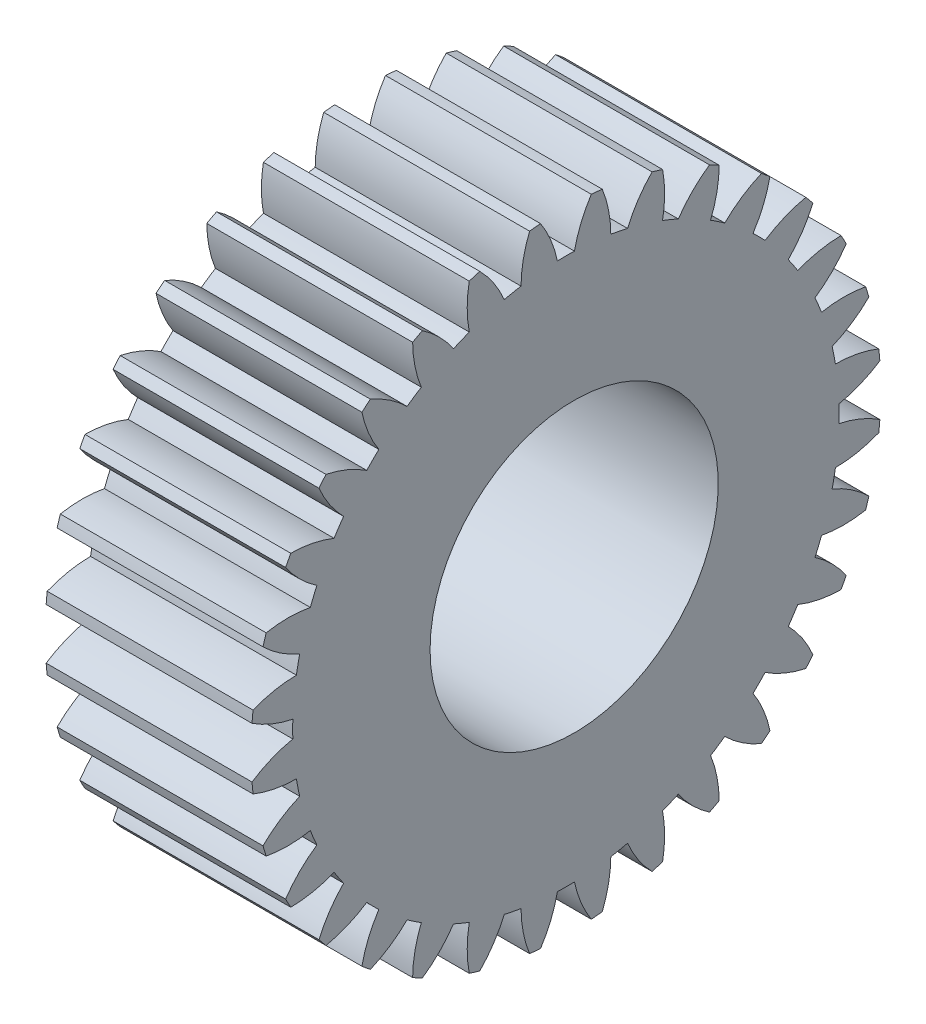
SolidWorks part; units mm, degrees
ref_plane "Plane1" through (0, 0, 0) normal (0, 0, 1) x (1, 0, 0)
ref_plane "Plane2" through (0, 0, 0) normal (0, 1, 0) x (1, 0, 0)
ref_plane "Plane3" through (0, 0, 0) normal (1, 0, 0) x (0, 0, -1)
sketch "HoldingSke" plane through (0, 0, 0) normal (0, 1, 0) x (1, 0, 0)
  line L0 (0, 0) -> (0.9423, -0.5888)
  line L1 (-15, 0) -> (100, 0) construction
  line L2 (0, 0) -> (-2.1039, 2.3779)
  line L3 (0, 0) -> (-11.863, 4.5341)
  line L4 (0, 0) -> (7.3237, 4.5764)
  line L5 (0, 0) -> (-46.8476, -17.4728)
  line L6 (0, 0) -> (-8.2896, -5.593)
  line L7 (-2.1039, 2.3779) -> (8.6586, 51.2059)
  line L8 (-76.2, 54.61) -> (-76.1, 54.61)
  line L9 (-71.009, 38.7566) -> (-53.1078, 45.2721)
  line L10 (-76.2, 71.12) -> (104.1128, 71.12)
  line L11 (0, 0) -> (-10, 0)
  line L12 (-76.2, 101.6) -> (-76.166, 101.6)
  line L13 (24.9733, 27.94) -> (52.9518, 28.4284)
  line L14 (24.9733, 27.94) -> (24.9743, 27.94)
  line L15 (24.9733, 27.94) -> (100.4006, 29.5858)
  line L16 (-63.627, -0.9) -> (-12.827, -0.9)
  circle A0 centre (0, 0) radius 0.4
  circle A1 centre (0, 0) radius 13.274
  circle A2 centre (0, 0) radius 37.5
  circle A3 centre (0, 0) radius 0.4
  dimension "MHD" = 26.548
  dimension "Hub_dia" = 75
  dimension "Bore" = 0.8
  dimension "MBD" = 0.8
  dimension "Num_teeth" = 32
  dimension "Pitch" = 1.1111
  dimension "Overall_len" = 50
  dimension "Show_teeth" = 32
  dimension "Thickness" = 10
  dimension "OAL" = 50.0001
  dimension "T_dim" = 0.1
  dimension "Ap" = 20
  dimension "H" = 19.05
  dimension "Pitch_radius" = 180.3128
  dimension "Width" = 10
  dimension "Backlash" = 0.034
  dimension "Addendum_fac" = 1
  dimension "Dedendum_fac" = 1.25
  dimension "Clearance_fac" = 0.25
  dimension "Dedendum_add" = 0.001
  dimension "Module" = 0.9
sketch "BasProSke" plane through (0, 0, 0) normal (0, 1, 0) x (1, 0, 0)
  line L0 (-10, 0) -> (60, 0) construction
  line L1 (0, 0) -> (0, 15.3)
  line L2 (0, 0) -> (10, 0)
  line L3 (10, 0) -> (10, 15.3)
  line L4 (10, 15.3) -> (0, 15.3)
  dimension "Thickness" = 10
  dimension "Diameter" = 30.6
revolve "Base-Revolve" add sketch "BasProSke" angle 360 about L0
sketch "TooCutSke" plane through (0, 0, 0) normal (1, 0, 0) x (0, 0, -1)
  line L1 (0, 0) -> (0, 107) construction
  line L2 (0, 0) -> (-0.7661, 14.3796) construction
  line L3 (0, 0) -> (-2.82, 28.6324) construction
  line L4 (-0.7661, 14.3796) -> (-1.41, 14.3162) construction
  arc A0 (0.4155, 13.2675) -> (-0.4155, 13.2675) centre (0, 0) ccw
  arc A1 (1.2493, 15.2744) -> (-1.2493, 15.2744) centre (0, 0) ccw
  circle A2 centre (0, 0) radius 14.4 construction
  circle A3 centre (0, 0) radius 13.5316 construction
  arc A4 (-0.4155, 13.2675) -> (-1.2493, 15.2744) centre (-6.0561, 12.1007) ccw
  arc A5 (1.2493, 15.2744) -> (0.4155, 13.2675) centre (6.0561, 12.1007) ccw
  dimension "Root_dia" = 26.548
  dimension "Overcut_dia" = 30.6508
  dimension "Pitch_dia" = 28.8
  dimension "Base_dia" = 27.0631
  dimension "Flank_rad" = 5.76
  dimension "Half_ang" = 5.625
  dimension "Half_CT" = 0.6471
extrude "ToothCut" cut sketch "TooCutSke" along normal through all
fillet "Breaks" [suppressed] radius 0.018
fillet "RootFillets" [suppressed] radius 0.226
pattern_circular "TeethCuts" count 32 every 11.25 about axis through (-10, 0, 0) along (1, 0, 0) of "ToothCut", "RootFillets", "Breaks"
sketch "HubNeaOneSke" plane through (0, 0, 0) normal (-1, 0, 0) x (0, 0, 1)
  circle A0 centre (0, 0) radius 13.274
  dimension "Diameter" = 26.548
extrude "HubNearOne" [suppressed] add sketch "HubNeaOneSke" along normal blind 40.0001
sketch "HubNeaBotSke" plane through (0, 0, 0) normal (-1, 0, 0) x (0, 0, 1)
  circle A0 centre (0, 0) radius 13.274
  dimension "Diameter" = 26.548
extrude "HubNearBoth" [suppressed] add sketch "HubNeaBotSke" along normal blind 20
ref_plane "FarPln" through (10, 0, 0) normal (1, 0, 0) x (0, 0, -1)
sketch "HubFarSke" plane through (10, 0, 0) normal (1, 0, 0) x (0, 0, -1)
  circle A0 centre (0, 0) radius 13.274
  dimension "Diameter" = 26.548
extrude "HubFar" [suppressed] add sketch "HubFarSke" along normal blind 20
sketch "BorSke" plane through (0, 0, 0) normal (1, 0, 0) x (0, 0, -1)
  circle A0 centre (0, 0) radius 0.4
  dimension "Diameter" = 0.8
extrude "Bore" cut sketch "BorSke" along normal mid plane 100.0001
sketch "KeySke" plane through (0, 0, 0) normal (1, 0, 0) x (0, 0, -1)
  line L0 (-0.05, 0) -> (-0.05, 0.5)
  line L1 (-0.05, 0.5) -> (0.05, 0.5)
  line L2 (0.05, 0.5) -> (0.05, 0)
  line L3 (0, 0) -> (0, 34) construction
  line L4 (-0.05, 0) -> (0.05, 0)
  dimension "Offset" = 0.5
  dimension "Width" = 0.1
extrude "Keyway" [suppressed] cut sketch "KeySke" along normal mid plane 100.0001
pattern_circular "Keyway2" [suppressed] count 2 every 90 about axis through (-10, 0, 0) along (1, 0, 0)
sketch "Sketch1" plane through (0, 0, 0) normal (-1, 0, 0) x (0, 0, 1)
  circle A0 centre (-0.4, 0) radius 7
  circle A1 centre (0, 0) radius 0.4 construction
  dimension "D1" = 14
extrude "Cut-Extrude1" cut sketch "Sketch1" against normal blind 10
equation "' \"Module@HoldingSke\" = 6.35"
equation "' \"Num_teeth@HoldingSke\" = 12"
equation "' \"Ap@HoldingSke\" =  20"
equation "' \"Ap@HoldingSke\" = 20"
equation "' \"Width@HoldingSke\" = 0.5 * 25.4"
equation "' \"Hub_dia@HoldingSke\"= 1 * 25.4"
equation "' \"Hub_dia@HoldingSke\" = 1 * 25.4"
equation "' \"Overall_len@HoldingSke\" = 1.0 * 25.4"
equation "' \"Bore@HoldingSke\" = 0.75 * 25.4"
equation "' \"T_dim@HoldingSke\" = 0.1 * 25.4"
equation "' \"Width@KeySke\" = 0.25 * 25.4"
equation "' \"Show_teeth@HoldingSke\" = 13"
equation "' \"Backlash@HoldingSke\" = 0.009 * 25.4"
equation "' \"Addendum_fac@HoldingSke\" = 1.0"
equation "' \"Dedendum_fac@HoldingSke\" = 1.25"
equation "' \"Dedendum_add@HoldingSke\" = 0.00005 * 25.4"
equation "' \"Clearance_fac@HoldingSke\" = 0.25"
equation "\"Pitch@HoldingSke\" = 1 / \"Module@HoldingSke\""
equation "\"Overcut_dia@TooCutSke\" = (\"Num_teeth@HoldingSke\" + 2 * \"Addendum_fac@HoldingSke\") / \"Pitch@HoldingSke\" + 0.002 * 25.4"
equation "\"Pitch_dia@TooCutSke\" = \"Num_teeth@HoldingSke\" / \"Pitch@HoldingSke\""
equation "\"Base_dia@TooCutSke\" = \"Num_teeth@HoldingSke\" / \"Pitch@HoldingSke\" * cos((\"Ap@HoldingSke\"  * 3.14159265 / 180))"
equation "\"Root_dia@TooCutSke\" = (\"Num_teeth@HoldingSke\" + 2) / \"Pitch@HoldingSke\" - 2 * (\"Addendum_fac@HoldingSke\" + \"Dedendum_fac@HoldingSke\") / \"Pitch@HoldingSke\" - \"Dedendum_add@HoldingSke\" * 2"
equation "\"Half_ang@TooCutSke\" = 180 / \"Num_teeth@HoldingSke\""
equation "\"Half_CT@TooCutSke\" = \"Num_teeth@HoldingSke\" / \"Pitch@HoldingSke\" * sin((3.14159265 / 2 / \"Num_teeth@HoldingSke\")) / 2 - 7 * \"Backlash@HoldingSke\" / 4"
equation "\"Flank_rad@TooCutSke\" = \"Num_teeth@HoldingSke\" / \"Pitch@HoldingSke\" / 5"
equation "\"Radius@RootFillets\" = \"Clearance_fac@HoldingSke\" / \"Pitch@HoldingSke\" + \"Dedendum_add@HoldingSke\""
equation "\"Break_rad@Breaks\" = 0.02 / \"Pitch@HoldingSke\""
equation "\"Thickness@HoldingSke\" = \"Width@HoldingSke\""
equation "\"OAL@HoldingSke\" = \"Thickness@HoldingSke\""
equation "\"MHD@HoldingSke\" = (\"Num_teeth@HoldingSke\" + 2) / \"Pitch@HoldingSke\" - 2 * (\"Addendum_fac@HoldingSke\" + \"Dedendum_fac@HoldingSke\")  / \"Pitch@HoldingSke\" - \"Dedendum_add@HoldingSke\" * 2"
equation "\"MBD@HoldingSke\" = (\"Num_teeth@HoldingSke\" + 2) / \"Pitch@HoldingSke\" - 2 * (\"Addendum_fac@HoldingSke\" + \"Dedendum_fac@HoldingSke\")  / \"Pitch@HoldingSke\" - \"Dedendum_add@HoldingSke\" * 2 - 0.002 * 25.4"
equation "\"MHD@HoldingSke\" = ((sgn( \"MHD@HoldingSke\" - \"Hub_dia@HoldingSke\" )-1)*( \"MHD@HoldingSke\" - \"Hub_dia@HoldingSke\" ))/-2+ \"Hub_dia@HoldingSke\""
equation "\"MBD@HoldingSke\" = ((sgn( \"MBD@HoldingSke\" - \"Bore@HoldingSke\" )-1)*( \"MBD@HoldingSke\" - \"Bore@HoldingSke\" ))/-2+ \"Bore@HoldingSke\""
equation "\"OAL@HoldingSke\" = ((sgn( \"OAL@HoldingSke\" - \"Overall_len@HoldingSke\" )+1)*( \"OAL@HoldingSke\" - \"Overall_len@HoldingSke\" ))/2 + \"Overall_len@HoldingSke\" + 0.000002 * 25.4"
equation "\"Num_teeth@TeethCuts\" = int( \"Show_teeth@HoldingSke\" ) + 1"
equation "\"Num_teeth@TeethCuts\" = ((sgn( \"Num_teeth@TeethCuts\" - \"Num_teeth@HoldingSke\" )-1)*( \"Num_teeth@TeethCuts\" - \"Num_teeth@HoldingSke\" ))/-2+ \"Num_teeth@HoldingSke\""
equation "\"Num_teeth@TeethCuts\" = ((sgn( \"Num_teeth@TeethCuts\" - 2.0)+1)*( \"Num_teeth@TeethCuts\" - 2.0))/2 +2.0"
equation "\"Angle@TeethCuts\" = 360.0 / \"Num_teeth@HoldingSke\""
equation "\"Diameter@BasProSke\" = (\"Num_teeth@HoldingSke\" + 2 * \"Addendum_fac@HoldingSke\") / \"Pitch@HoldingSke\""
equation "\"Thickness@BasProSke\"  = \"Thickness@HoldingSke\""
equation "' \"Fillet_rad@BasProSke\" =  \"Thickness@HoldingSke\" * 0.05"
equation "' \"Fillet_rad@BasProSke\" = \"Thickness@HoldingSke\" * 0.05"
equation "\"MHD@HoldingSke\" = ((sgn( \"MHD@HoldingSke\" - \"Root_dia@TooCutSke\" )-1)*( \"MHD@HoldingSke\" - \"Root_dia@TooCutSke\" ))/-2+ \"Root_dia@TooCutSke\""
equation "\"Diameter@HubNeaOneSke\" = \"MHD@HoldingSke\""
equation "\"Length@HubNearOne\" = \"OAL@HoldingSke\" - \"Thickness@BasProSke\""
equation "\"Diameter@HubNeaBotSke\" = \"MHD@HoldingSke\""
equation "\"Length@HubNearBoth\" = ( \"OAL@HoldingSke\" - \"Thickness@BasProSke\" ) / 2.0"
equation "\"Thickness@FarPln\" = \"Thickness@BasProSke\""
equation "\"Diameter@HubFarSke\" = \"MHD@HoldingSke\""
equation "\"Length@HubFar\" = ( \"OAL@HoldingSke\" - \"Thickness@BasProSke\" ) / 2.0"
equation "\"Diameter@BorSke\" = \"MBD@HoldingSke\""
equation "\"D1@Bore\" = \"OAL@HoldingSke\" * 2.0"
equation "\"D1@Keyway\" = \"OAL@HoldingSke\" * 2.0"
equation "\"Offset@KeySke\" = \"T_dim@HoldingSke\" + \"MBD@HoldingSke\" / 2.0"
